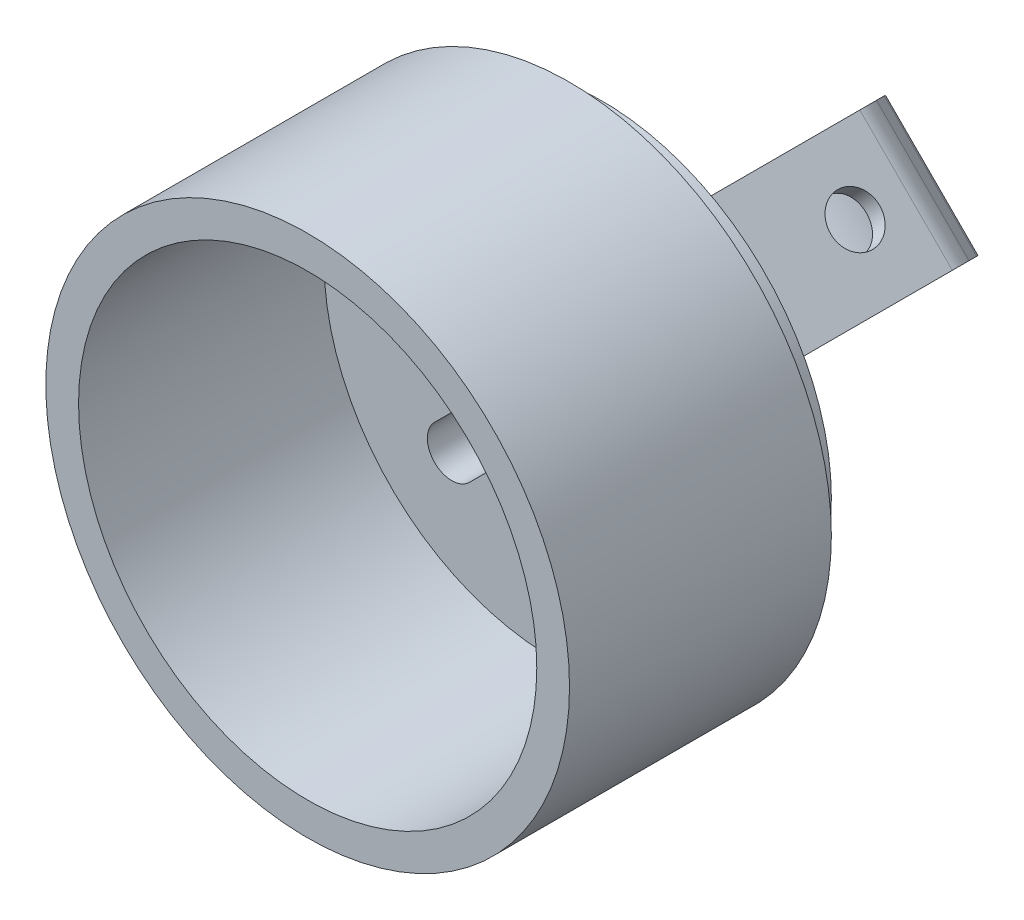
SolidWorks part; units mm, degrees
ref_plane "Front Plane" through (0, 0, 0) normal (0, 0, 1) x (1, 0, 0)
ref_plane "Top Plane" through (0, 0, 0) normal (0, 1, 0) x (1, 0, 0)
ref_plane "Right Plane" through (0, 0, 0) normal (1, 0, 0) x (0, 0, -1)
ref_plane "Plane1" through (0, 0, 0) normal (-0.7071, 0.7071, 0) x (0.7071, 0.7071, 0)
sketch "Sketch1" plane through (0, 0, 0) normal (0, 0, 1) x (1, 0, 0)
  line L0 (6.1872, -6.1872) -> (-6.1872, 6.1872) construction
  line L1 (5.1265, -7.2478) -> (0.7765, -2.8978)
  line L2 (7.2478, -5.1265) -> (2.8978, -0.7765)
  line L3 (0, 0) -> (4.2534, 0) construction
  line L5 (-6.1872, -6.1872) -> (6.1872, 6.1872) construction
  line L6 (-5.1265, -7.2478) -> (-0.7765, -2.8978)
  line L7 (-7.2478, -5.1265) -> (-2.8978, -0.7765)
  line L8 (0.7765, 2.8978) -> (5.1265, 7.2478)
  line L9 (2.8978, 0.7765) -> (7.2478, 5.1265)
  line L10 (-2.8978, 0.7765) -> (-7.2478, 5.1265)
  line L11 (-0.7765, 2.8978) -> (-5.1265, 7.2478)
  circle A0 centre (0, 0) radius 14
  circle A1 centre (0, 8) radius 1
  circle A2 centre (9.5, 0) radius 1
  circle A3 centre (0, -8) radius 1
  circle A4 centre (-9.5, 0) radius 1
  arc A5 (5.1265, -7.2478) -> (7.2478, -5.1265) centre (6.1872, -6.1872) ccw
  arc A6 (-5.1265, 7.2478) -> (-7.2478, 5.1265) centre (-6.1872, 6.1872) ccw
  arc A7 (-5.1265, -7.2478) -> (-7.2478, -5.1265) centre (-6.1872, -6.1872) cw
  arc A8 (5.1265, 7.2478) -> (7.2478, 5.1265) centre (6.1872, 6.1872) cw
  circle A9 centre (0, 0) radius 3
  point P7 (0, 0)
  point P14 (0, 0)
  point P26 (0, 0)
  dimension "D1" = 28
  dimension "D3" = 2
  dimension "D7" = 1.5
  dimension "D8" = 6
  dimension "D4" = 8
  dimension "D5" = 135
  dimension "D6" = 17.5
  dimension "D2" = 8
  dimension "D9" = 19
  dimension "D10" = 9.5
extrude "Boss-Extrude1" add sketch "Sketch1" along normal blind 3 contours A0 A9 L8 A8 L9 L2 A5 L1 L6 A7 L7 L10 A6 L11 A4 A3 A2 A1 | A9
sketch "Sketch2" plane through (0, 0, 3) normal (0, 0, 1) x (1, 0, 0)
  circle A0 centre (0, 0) radius 14
  circle A1 centre (0, 0) radius 16
  dimension "D1" = 28
  dimension "D2" = 32
extrude "Boss-Extrude2" add sketch "Sketch2" along normal blind 15 and the other way blind 1
sketch "Sketch3" plane through (0, 0, 0) normal (-0.7071, 0.7071, 0) x (0.7071, 0.7071, 0)
  line L0 (14, 0) -> (-14, 0) construction
  line L1 (-9.05, 9.05) -> (-9.05, 0)
  line L2 (9.05, 9.05) -> (9.05, 0)
  line L3 (-9.05, 0) -> (9.05, 0)
  line L4 (-9.05, 9.05) -> (-9.05, 12.166)
  line L5 (-8.3963, 13.645) -> (-6.092, 15.7426)
  line L7 (0, 9.2788) -> (0, 21.1291) construction
  line L8 (9.05, 9.05) -> (9.05, 12.166)
  line L9 (8.3963, 13.645) -> (6.092, 15.7426)
  arc A0 (6.092, 15.7426) -> (-6.092, 15.7426) centre (0, 9.05) ccw
  circle A1 centre (0, 9.05) radius 8.05
  arc A2 (-9.05, 12.166) -> (-8.3963, 13.645) centre (-7.05, 12.166) cw
  arc A3 (9.05, 12.166) -> (8.3963, 13.645) centre (7.05, 12.166) ccw
  point P12 (-9.05, 13.05)
  dimension "D1" = 18.1
  dimension "D2" = 16.1
  dimension "D5" = 2
  dimension "D3" = 4
  dimension "D4" = 4
extrude "Boss-Extrude3" add sketch "Sketch3" along normal mid plane 8
sketch "Sketch4" plane through (0, 0, 0) normal (0, 0, -1) x (-1, 0, 0)
  circle A0 centre (0, 0) radius 2.5
  dimension "D1" = 5
extrude "Cut-Extrude1" cut sketch "Sketch4" against normal blind 30 and the other way blind 10
sketch "Sketch5" plane through (6.3993, 6.3993, 0) normal (0.7071, 0.7071, 0) x (0, 0, -1)
  line L0 (9.05, 4) -> (9.05, -4) construction
  circle A0 centre (9.05, 0) radius 1.5
  dimension "D1" = 3
  dimension "D2" = 0
extrude "Cut-Extrude2" cut sketch "Sketch5" against normal through all
